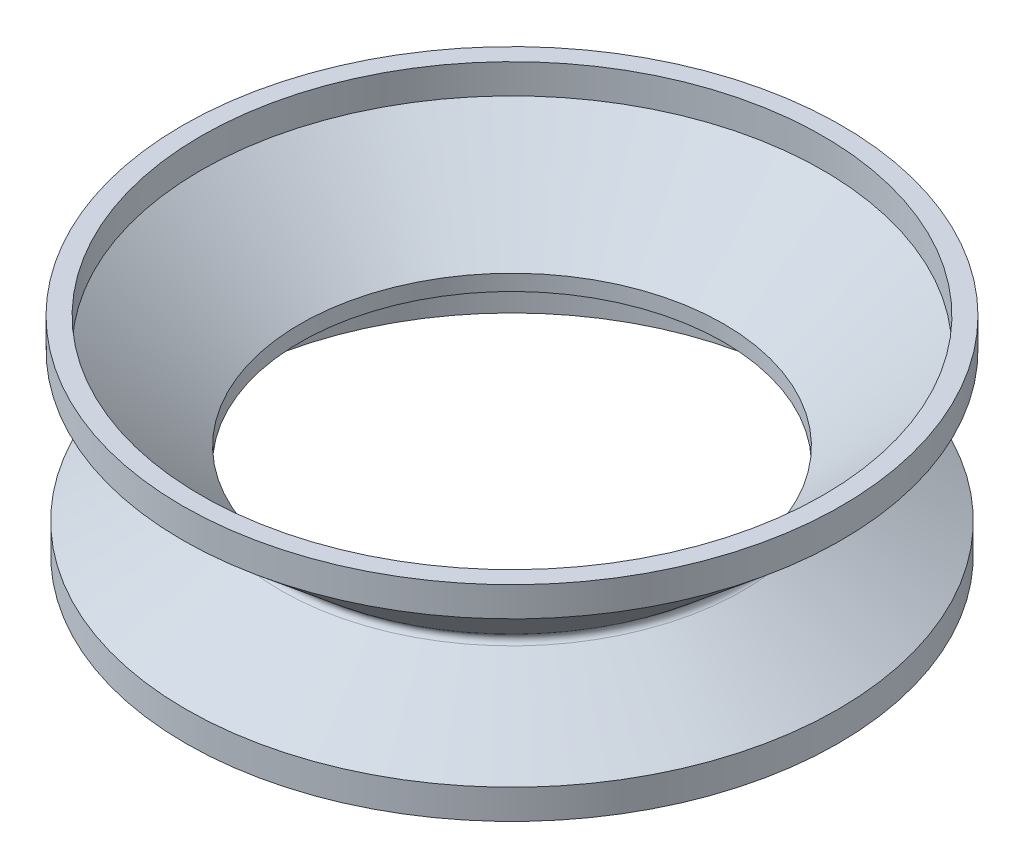
SolidWorks part; units mm, degrees
ref_plane "Front Plane" through (0, 0, 0) normal (0, 0, 1) x (1, 0, 0)
ref_plane "Top Plane" through (0, 0, 0) normal (0, 1, 0) x (1, 0, 0)
ref_plane "Right Plane" through (0, 0, 0) normal (1, 0, 0) x (0, 0, -1)
sketch "Sketch1" plane through (0, 0, 0) normal (0, 0, 1) x (1, 0, 0)
  line L0 (-42.6436, 0) -> (43.9692, 0) construction
  line L1 (0.6628, 0) -> (-6.4877, 6)
  line L2 (0.6628, 0) -> (-6.2654, -4)
  line L3 (1.4628, -0.6928) -> (-4.2654, -4)
  line L5 (-6.4877, 6) -> (-5.2432, 6)
  line L6 (-6.2654, -4) -> (-4.2654, -4)
  line L7 (15.7568, 5.609) -> (15.7568, -9.609) construction
  line L8 (2.3996, -0.152) -> (-16.3835, 15.6089) construction
  line L9 (0.6628, 0) -> (-17.0263, 14.8429) construction
  line L10 (0.6628, 0) -> (-17.9865, -10.7671) construction
  line L11 (2.3996, -0.152) -> (-17.4865, -11.6332) construction
  line L12 (0.6628, 0) -> (2.2628, 0) construction
  line L13 (1.4628, -0.6928) -> (1.4628, 0.373)
  line L14 (1.4628, 0.373) -> (-5.2432, 6)
  point P11 (1.4628, 0)
  dimension "D1" = 40
  dimension "D2" = 30
  dimension "D4" = 6
  dimension "D5" = 4
  dimension "D6" = 21
  dimension "D7" = 1.6
  dimension "D8" = 0.8
  dimension "D3" = 1
revolve "Revolve1" add sketch "Sketch1" angle 360 about L7
scale "Scale1" [suppressed]
fillet "Fillet2" radius 0.4 1 edges at (15.7568, 0, 15.0941)
sketch "Sketch2" plane through (0, 6, 0) normal (0, 1, 0) x (1, 0, 0)
  circle A0 centre (15.7568, 0) radius 22.2446 construction
  circle A1 centre (15.7568, 0) radius 21 construction
  circle A2 centre (15.7568, 0) radius 22.2446
  circle A3 centre (15.7568, 0) radius 21
extrude "Boss-Extrude1" add sketch "Sketch2" along normal blind 2
sketch "Sketch3" plane through (0, -4, 0) normal (0, -1, 0) x (1, 0, 0)
  circle A0 centre (15.7568, 0) radius 20.0223 construction
  circle A1 centre (15.7568, 0) radius 22.0223 construction
  circle A2 centre (15.7568, 0) radius 20.0223
  circle A3 centre (15.7568, 0) radius 22.0223
extrude "Boss-Extrude2" add sketch "Sketch3" along normal blind 2
